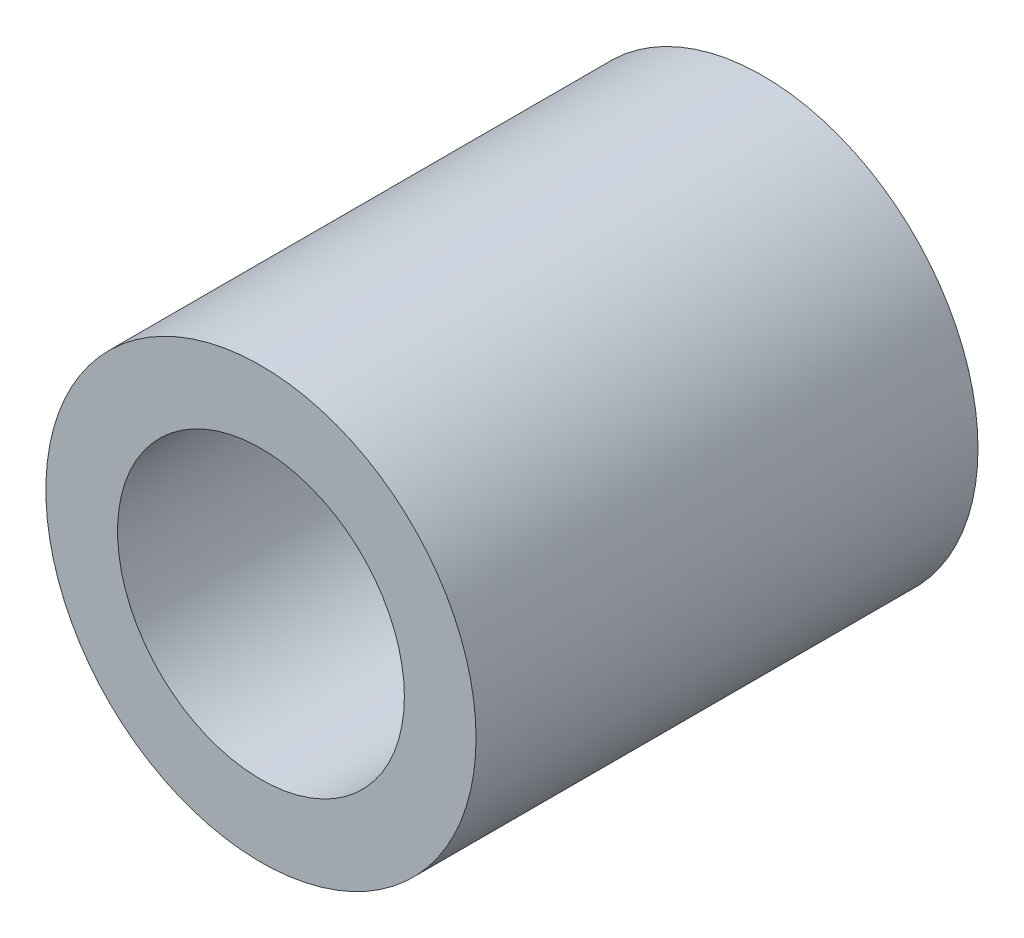
SolidWorks part; units mm, degrees
ref_plane "Plan de face" through (0, 0, 0) normal (0, 0, 1) x (1, 0, 0)
ref_plane "Plan de dessus" through (0, 0, 0) normal (0, 1, 0) x (1, 0, 0)
ref_plane "Plan de droite" through (0, 0, 0) normal (1, 0, 0) x (0, 0, -1)
sketch "Esquisse1" plane through (0, 0, 0) normal (0, 0, 1) x (1, 0, 0)
  circle A0 centre (0, 0) radius 2
  circle A1 centre (0, 0) radius 3
  dimension "D1" = 4
  dimension "D2" = 6
extrude "Boss.-Extru.1" add sketch "Esquisse1" along normal blind 7
